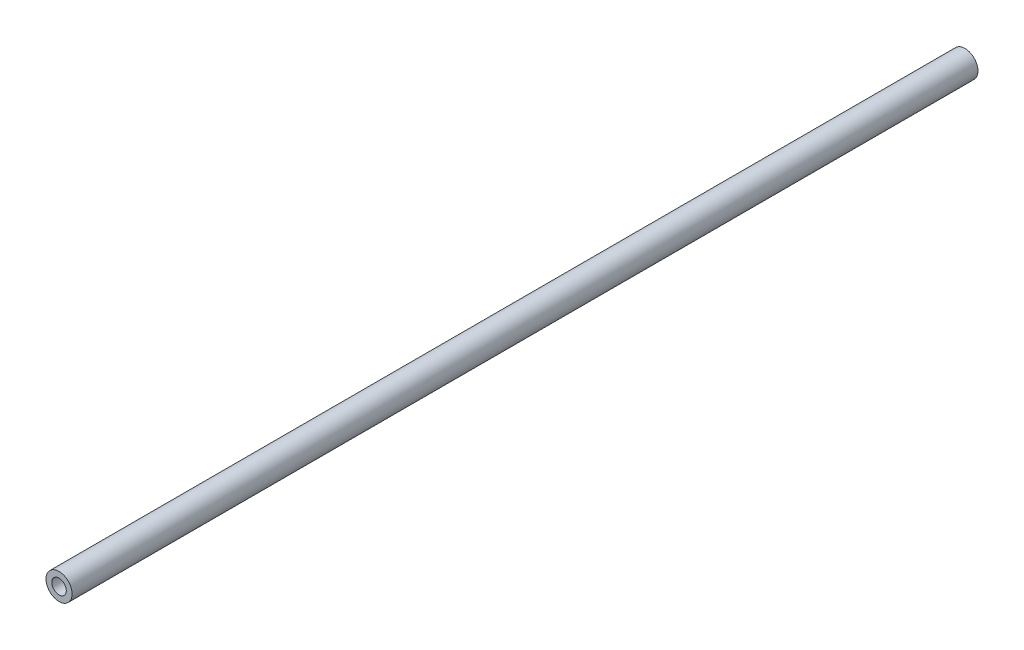
SolidWorks part; units mm, degrees
ref_plane "Front Plane" through (0, 0, 0) normal (0, 0, 1) x (1, 0, 0)
ref_plane "Top Plane" through (0, 0, 0) normal (0, 1, 0) x (1, 0, 0)
ref_plane "Right Plane" through (0, 0, 0) normal (1, 0, 0) x (0, 0, -1)
sketch "Sketch32" plane through (0, 0, 0) normal (0, 0, 1) x (1, 0, 0)
  circle A0 centre (0, 0) radius 8.55
  circle A1 centre (0, 0) radius 4.765
  dimension "D1" = 17.1
  dimension "D2" = 9.53
extrude "Boss-Extrude1" add sketch "Sketch32" along normal blind 593.65
